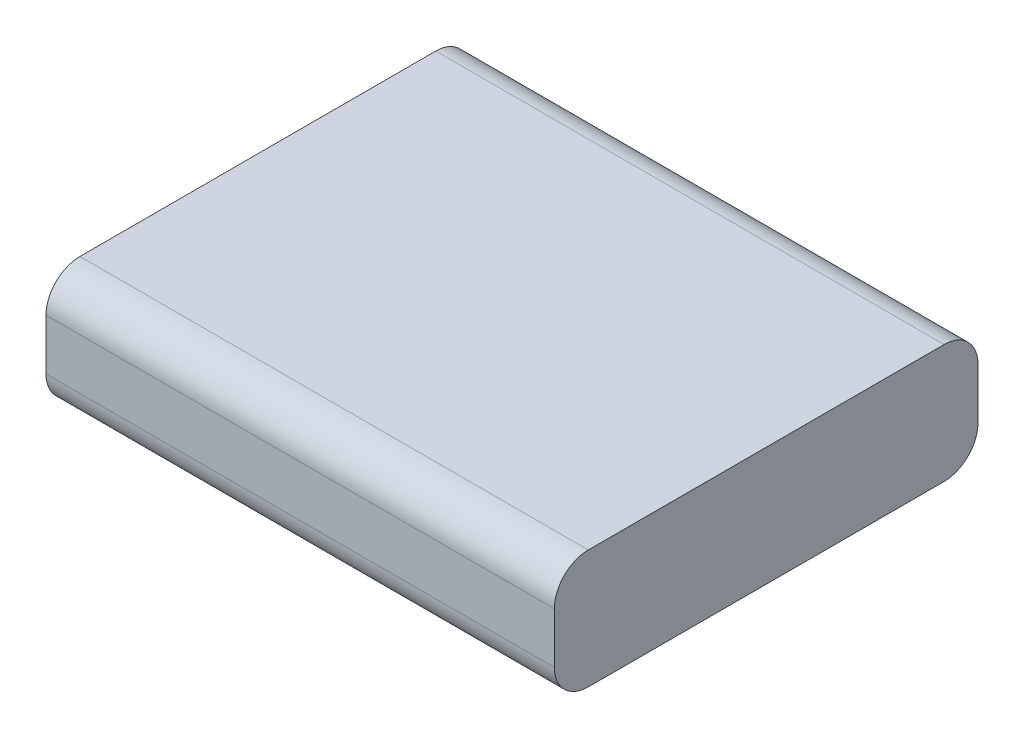
SolidWorks part; units mm, degrees
ref_plane "Front Plane" through (0, 0, 0) normal (0, 0, 1) x (1, 0, 0)
ref_plane "Top Plane" through (0, 0, 0) normal (0, 1, 0) x (1, 0, 0)
ref_plane "Right Plane" through (0, 0, 0) normal (1, 0, 0) x (0, 0, -1)
sketch "Эскиз1" plane through (0, 0, 0) normal (0, 1, 0) x (1, 0, 0)
  line L1 (-15, 12.5) -> (15, 12.5)
  line L2 (-15, 12.5) -> (-15, -12.5)
  line L3 (-15, -12.5) -> (15, -12.5)
  line L4 (15, 12.5) -> (15, -12.5)
  line L5 (-15, 12.5) -> (15, -12.5) construction
  line L6 (-15, -12.5) -> (15, 12.5) construction
  point P0 (0, 0)
  dimension "D1" = 25
  dimension "D2" = 30
extrude "Бобышка-Вытянуть1" add sketch "Эскиз1" along normal blind 7
fillet "Скругление1" radius 2 4 edges at (0, 0, -12.5) (0, 0, 12.5) (0, 7, -12.5) (0, 7, 12.5)
